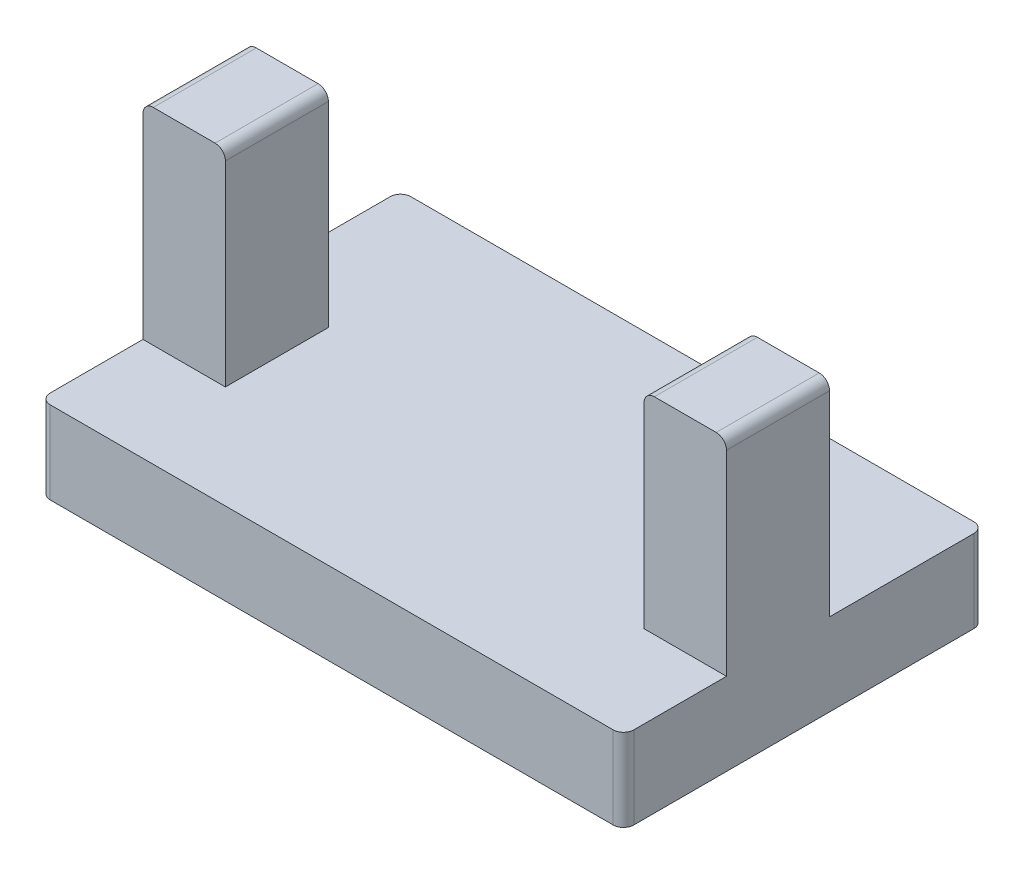
SolidWorks part; units mm, degrees
material "ABS"
ref_plane "Front Plane" through (0, 0, 0) normal (0, 0, 1) x (1, 0, 0)
ref_plane "Top Plane" through (0, 0, 0) normal (0, 1, 0) x (1, 0, 0)
ref_plane "Right Plane" through (0, 0, 0) normal (1, 0, 0) x (0, 0, -1)
sketch "Sketch1" plane through (0, 0, 0) normal (0, 1, 0) x (1, 0, 0)
  line L1 (-28.32, 17.5) -> (28.32, 17.5)
  line L2 (-28.32, 17.5) -> (-28.32, -17.5)
  line L3 (-28.32, -17.5) -> (28.32, -17.5)
  line L4 (28.32, 17.5) -> (28.32, -17.5)
  line L5 (-28.32, 17.5) -> (28.32, -17.5) construction
  line L6 (-28.32, -17.5) -> (28.32, 17.5) construction
  point P0 (0, 0)
  dimension "D1" = 56.64
  dimension "D2" = 35
extrude "Boss-Extrude1" add sketch "Sketch1" along normal blind 8
sketch "Sketch2" plane through (0, 8, 0) normal (0, 1, 0) x (1, 0, 0)
  line L1 (-28.32, -7.5) -> (-20.32, -7.5)
  line L2 (-28.32, -7.5) -> (-28.32, 2.5)
  line L3 (-28.32, 2.5) -> (-20.32, 2.5)
  line L4 (-20.32, -7.5) -> (-20.32, 2.5)
  line L10 (-28.32, -17.5) -> (28.32, -17.5) construction
  line L11 (-28.32, 17.5) -> (-28.32, -17.5) construction
  line L12 (0, -55) -> (0, 55) construction
  line L13 (28.32, 2.5) -> (20.32, 2.5)
  line L14 (20.32, -7.5) -> (20.32, 2.5)
  line L15 (28.32, -7.5) -> (20.32, -7.5)
  line L16 (28.32, -7.5) -> (28.32, 2.5)
  dimension "D1" = 10
  dimension "D2" = 8
  dimension "D3" = 10
extrude "Boss-Extrude2" add sketch "Sketch2" along normal blind 20
fillet "Fillet1" radius 1 8 edges at (-28.32, 4, -17.5) (-28.32, 4, 17.5) (28.32, 4, -17.5) (28.32, 4, 17.5) (20.32, 28, 2.5) (28.32, 28, 2.5) (-28.32, 28, 2.5) (-20.32, 28, 2.5)
hole_wizard "M4 Clearance Hole1" [suppressed] positions "Sketch6" profile "Sketch7" hole size "M4" standard "ANSI Metric"
sketch "Sketch6" plane through (0, 0, 7.5) normal (0, 0, 1) x (1, 0, 0)
  line L1 (-20.32, 36) -> (-20.32, 17) construction
  line L4 (-28.32, 17) -> (-20.32, 17) construction
  point P0 (-24.32, 31.9654)
  point P2 (-24.32, 19.63)
  dimension "D1" = 4
  dimension "D2" = 2.63
sketch "Sketch7" plane through (-24.32, 31.9654, 7.5) normal (1, 0, 0) x (0, -1, 0)
  line L0 (0, 0) -> (0, 25)
  line L1 (0, 25) -> (2.25, 25)
  line L2 (2.25, 25) -> (2.25, 0)
  line L5 (2.25, 0) -> (0, 0)
  line L11 (0, -6.35) -> (0, 107.95) construction
  dimension "Thru Hole Dia." = 4.5
  dimension "Thru Hole Depth" = 25
mirror "Mirror2" [suppressed] about plane through (0, 0, 0) normal (1, 0, 0)
